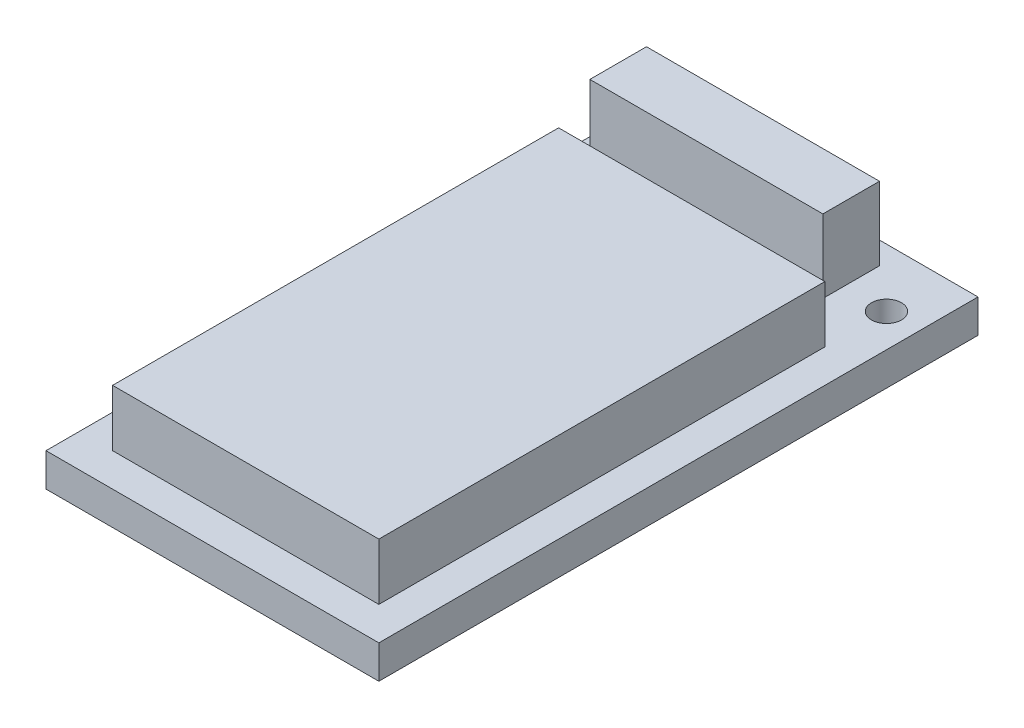
SolidWorks part; units mm, degrees
ref_plane "Plan de face" through (0, 0, 0) normal (0, 0, 1) x (1, 0, 0)
ref_plane "Plan de dessus" through (0, 0, 0) normal (0, 1, 0) x (1, 0, 0)
ref_plane "Plan de droite" through (0, 0, 0) normal (1, 0, 0) x (0, 0, -1)
ref_plane "Plan1" through (0, 1, 0) normal (0, 1, 0) x (1, 0, 0)
sketch "Esquisse1" plane through (0, 1, 0) normal (0, 1, 0) x (1, 0, 0)
  line L0 (-5, 9) -> (-5, -9)
  line L1 (-5, -9) -> (5, -9)
  line L2 (5, -9) -> (5, 9)
  line L3 (5, 9) -> (-5, 9)
extrude "Boss.-Extru.1" add sketch "Esquisse1" against normal blind 1
sketch "Esquisse2" plane through (0, 1, 0) normal (0, 1, 0) x (-1, 0, 0)
  line L0 (4, -5.4) -> (-4, -5.4)
  line L1 (-4, -5.4) -> (-4, 8)
  line L2 (-4, 8) -> (4, 8)
  line L3 (4, 8) -> (4, -5.4)
extrude "Boss.-Extru.2" add sketch "Esquisse2" along normal blind 1.7
sketch "Esquisse3" plane through (0, 1, 0) normal (0, 1, 0) x (-1, 0, 0)
  line L0 (4.29, -8.33) -> (-2.71, -8.33)
  line L1 (-2.71, -8.33) -> (-2.71, -6.63)
  line L2 (-2.71, -6.63) -> (4.29, -6.63)
  line L3 (4.29, -6.63) -> (4.29, -8.33)
extrude "Boss.-Extru.3" add sketch "Esquisse3" along normal blind 2.2
hole_wizard "Diamètre du perçage Ø0.9 (0.9)1" positions "Esquisse5" profile "Esquisse4" hole size "Ø0.9" standard "Ansi Metric"
sketch "Esquisse5" plane through (0, 0, 0) normal (0, -1, 0) x (-1, 0, 0)
  point P0 (-4, 7.25)
sketch "Esquisse4" plane through (4, 0, -7.25) normal (1, 0, 0) x (0, 0, -1)
  line L0 (0, 0) -> (0, 3.2)
  line L1 (0, 3.2) -> (0.45, 3.2)
  line L2 (0.45, 3.2) -> (0.45, 0)
  line L5 (0.45, 0) -> (0, 0)
  line L11 (0, -6.35) -> (0, 107.95) construction
  dimension "Diamètre du perçage jusqu'au prochain" = 0.9
  dimension "Profondeur du perçage jusqu'au prochain" = 3.2
